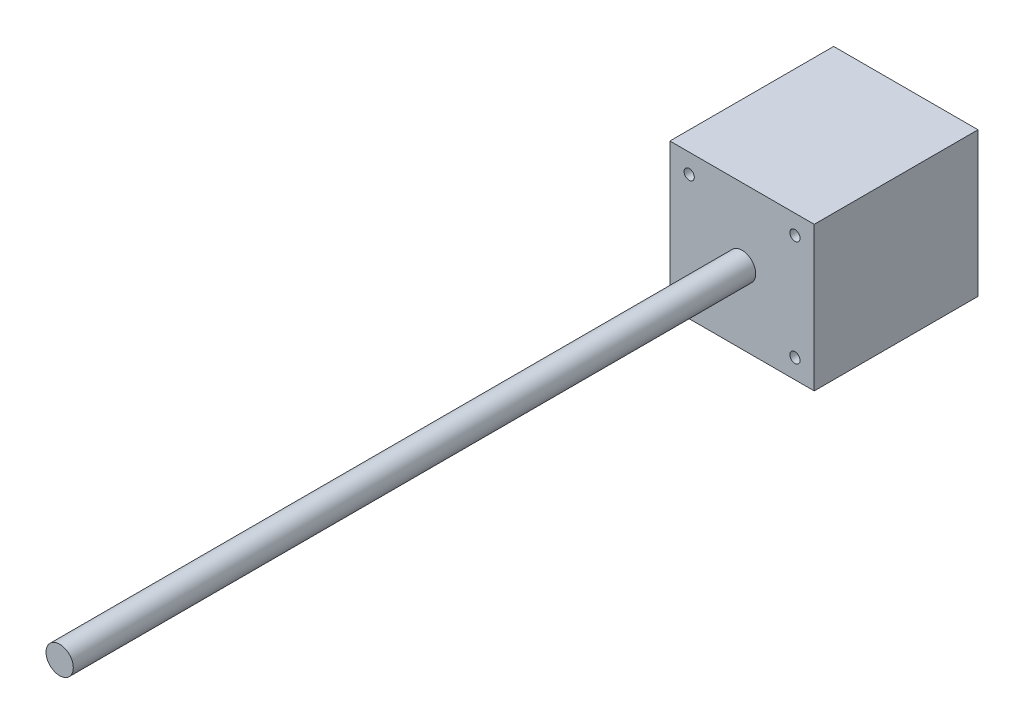
SolidWorks part; units mm, degrees
ref_plane "Front Plane" through (0, 0, 0) normal (0, 0, 1) x (1, 0, 0)
ref_plane "Top Plane" through (0, 0, 0) normal (0, 1, 0) x (1, 0, 0)
ref_plane "Right Plane" through (0, 0, 0) normal (1, 0, 0) x (0, 0, -1)
sketch "Sketch1" plane through (0, 0, 0) normal (0, 0, 1) x (1, 0, 0)
  line L5 (-21.15, -21.15) -> (21.15, -21.15)
  line L6 (-21.15, -21.15) -> (-21.15, 21.15)
  line L7 (-21.15, 21.15) -> (21.15, 21.15)
  line L8 (21.15, -21.15) -> (21.15, 21.15)
  line L9 (-21.15, -21.15) -> (21.15, 21.15) construction
  line L10 (-21.15, 21.15) -> (21.15, -21.15) construction
  circle A0 centre (15.5, 15.5) radius 1.5
  circle A1 centre (-15.5, 15.5) radius 1.5
  circle A2 centre (-15.5, -15.5) radius 1.5
  circle A3 centre (15.5, -15.5) radius 1.5
  point P0 (0, 0)
  point P15 (0, 0)
  point P16 (0, 0)
  dimension "D3" = 3
  dimension "D1" = 42.3
  dimension "D2" = 31
extrude "Boss-Extrude1" add sketch "Sketch1" along normal blind 48
sketch "Sketch2" plane through (0, 0, 48) normal (0, 0, 1) x (1, 0, 0)
  circle A0 centre (0, 0) radius 4
  dimension "D1" = 8
extrude "Boss-Extrude2" add sketch "Sketch2" along normal blind 200
